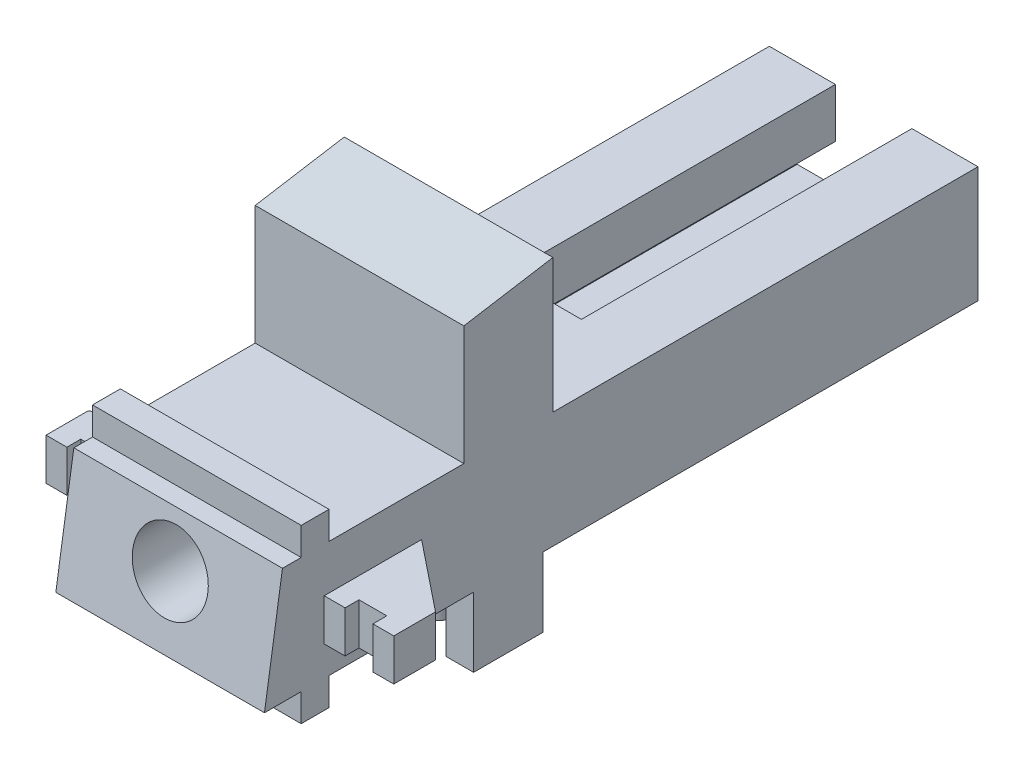
SolidWorks part; units mm, degrees
ref_plane "Front Plane" through (0, 0, 0) normal (0, 0, 1) x (1, 0, 0)
ref_plane "Top Plane" through (0, 0, 0) normal (0, 1, 0) x (1, 0, 0)
ref_plane "Right Plane" through (0, 0, 0) normal (1, 0, 0) x (0, 0, -1)
sketch "Sketch9" plane through (0, 0, 0) normal (0, 0, 1) x (1, 0, 0)
  line L1 (-7.5, 8.35) -> (7.5, 8.35)
  line L2 (-7.5, 8.35) -> (-7.5, 0)
  line L3 (-7.5, 0) -> (7.5, 0)
  line L4 (7.5, 8.35) -> (7.5, 0)
  line L5 (-7.5, 8.35) -> (7.5, 0) construction
  line L6 (-7.5, 0) -> (7.5, 8.35) construction
  point P0 (0, 4.175)
  point P19 (0, 0)
  dimension "D1" = 8.35
  dimension "D2" = 15
extrude "Boss-Extrude4" add sketch "Sketch9" along normal blind 50
sketch "Sketch7" plane through (0, 0, 0) normal (0, 0, 1) x (1, 0, 0)
  line L0 (-5.5, 2) -> (-5.5, 4.8)
  line L1 (-5.5, 4.8) -> (-2.75, 4.8)
  line L2 (-2.75, 4.8) -> (-2.75, 8.35)
  line L3 (-2.75, 8.35) -> (2.75, 8.35) construction
  line L4 (2.75, 8.35) -> (2.75, 4.8)
  line L5 (2.75, 4.8) -> (5.5, 4.8)
  line L6 (5.5, 4.8) -> (5.5, 2)
  line L7 (5.5, 2) -> (-5.5, 2)
  line L9 (7.5, 8.35) -> (-7.5, 8.35) construction
  line L11 (7.5, 0) -> (7.5, 8.35) construction
  line L13 (-2.75, 8.35) -> (2.75, 8.35)
  dimension "D1" = 2.8
  dimension "D2" = 2
  dimension "D3" = 11
  dimension "D4" = 5.5
  dimension "D5" = 2
extrude "Cut-Extrude4" cut sketch "Sketch7" along normal blind 23.76
sketch "Sketch21" plane through (-7.5, 0, 0) normal (-1, 0, 0) x (0, 0, 1)
  line L7 (50, 0) -> (51.2947, 0)
  line L8 (51.2947, 0) -> (50, 8.35)
  line L9 (50, 8.35) -> (50, 0)
extrude "Boss-Extrude9" add sketch "Sketch21" against normal up to surface (15 mm away) up to face at (7.5, 4.175, 25)
sketch "Sketch10" plane through (0, 0, 23.76) normal (0, 0, 1) x (1, 0, 0)
  line L0 (5.5, 2) -> (-5.5, 2) construction
  circle A0 centre (0, 4.7) radius 2.7
  dimension "D1" = 5.4
extrude "Cut-Extrude5" cut sketch "Sketch10" along normal up to surface (26.806 mm away)
sketch "Sketch12" plane through (7.5, 0, 0) normal (1, 0, 0) x (0, 0, -1)
  line L0 (-51.2947, 0) -> (0, 0) construction
  line L1 (-47, 5.14) -> (-44, 5.14)
  line L2 (-47, 5.14) -> (-47, 2.14)
  line L3 (-47, 2.14) -> (-44, 2.14)
  line L4 (-44, 5.14) -> (-44, 2.14)
  line L5 (-47, 5.14) -> (-44, 2.14) construction
  line L6 (-47, 2.14) -> (-44, 5.14) construction
  point P0 (-45.5, 3.64)
  dimension "D1" = 3
  dimension "D2" = 3
  dimension "D3" = 2.14
  dimension "D4" = 3
extrude "Boss-Extrude5" add sketch "Sketch12" along normal blind 5
ref_plane "Plane1" through (0, 0, 0) normal (1, 0, 0) x (0, 0, -1)
sketch "Sketch13" plane through (0, 0, 47) normal (0, 0, 1) x (1, 0, 0)
  line L1 (9, 5.14) -> (11, 5.14)
  line L2 (9, 5.14) -> (9, 2.14)
  line L3 (9, 2.14) -> (11, 2.14)
  line L4 (11, 5.14) -> (11, 2.14)
  line L6 (12.5, 5.14) -> (7.5, 5.14) construction
  line L7 (12.5, 2.14) -> (7.5, 2.14) construction
  point P8 (10, 5.14)
  point P9 (10, 5.14)
  dimension "D2" = 2
extrude "Cut-Extrude6" cut sketch "Sketch13" against normal blind 1
mirror "Mirror2" about plane through (0, 0, 0) normal (1, 0, 0) of "Boss-Extrude5"
mirror "Mirror4" about plane through (0, 0, 0) normal (1, 0, 0) of "Cut-Extrude6"
sketch "Sketch14" plane through (0, 5.14, 0) normal (0, 1, 0) x (1, 0, 0)
  line L0 (12.5, -44) -> (7.5, -40)
  line L1 (7.5, -50) -> (7.5, 0) construction
  line L2 (7.5, -40) -> (7.5, -44)
  line L3 (7.5, -44) -> (12.5, -44)
  dimension "D1" = 4
extrude "Boss-Extrude6" add sketch "Sketch14" against normal up to surface (3 mm away) up to face at (10, 2.14, 46)
mirror "Mirror5" about plane through (0, 0, 0) normal (1, 0, 0) of "Boss-Extrude6"
sketch "Sketch22" plane through (-7.5, 0, 0) normal (-1, 0, 0) x (0, 0, 1)
  line L0 (51.2947, 0) -> (0, 0) construction
  line L1 (48.6551, 0) -> (46.6551, 0)
  line L2 (48.6551, 0) -> (48.6551, -2)
  line L3 (48.6551, -2) -> (46.6551, -2)
  line L4 (46.6551, 0) -> (46.6551, -2)
  line L5 (48.6551, 0) -> (46.6551, -2) construction
  line L6 (48.6551, -2) -> (46.6551, 0) construction
  line L7 (50.6474, 4.175) -> (0, 4.175) construction
  line L8 (51.2947, 0) -> (50, 8.35) construction
  line L9 (0, 8.35) -> (0, 0) construction
  line L10 (48.6551, 10.35) -> (46.6551, 8.35) construction
  line L11 (48.6551, 8.35) -> (46.6551, 10.35) construction
  line L12 (46.6551, 8.35) -> (46.6551, 10.35)
  line L13 (48.6551, 10.35) -> (46.6551, 10.35)
  line L14 (48.6551, 8.35) -> (48.6551, 10.35)
  line L15 (48.6551, 8.35) -> (46.6551, 8.35)
  line L16 (50, 8.35) -> (0, 8.35) construction
  point P0 (47.6551, -1)
  point P18 (47.6551, 9.35)
  dimension "D1" = 2
extrude "Boss-Extrude10" add sketch "Sketch22" against normal up to surface (15 mm away) up to face at (7.5, 4.175, 25.3237)
sketch "Sketch23" plane through (0, 0, 0) normal (0, -1, 0) x (1, 0, 0)
  line L0 (-5.5, 23.76) -> (0, 23.76) construction
  line L2 (-7.5, 23.76) -> (7.5, 23.76) construction
  line L3 (7.5, 46.6551) -> (7.5, 0) construction
  line L4 (-7.5, 46.6551) -> (-7.5, 0) construction
  circle A0 centre (0, 29.26) radius 2.5
  dimension "D2" = 5
  dimension "D1" = 5.5
extrude "Cut-Extrude7" cut sketch "Sketch23" against normal up to surface (2 mm away)
sketch "Sketch24" plane through (0, 0, 0) normal (0, -1, 0) x (1, 0, 0)
  line L0 (5.5, 36.26) -> (7.5, 36.26)
  line L1 (7.5, 46.6551) -> (7.5, 0) construction
  line L2 (7.5, 36.26) -> (7.5, 31.26)
  line L3 (7.5, 31.26) -> (5.5, 31.26)
  line L4 (5.5, 36.26) -> (-5.5, 36.26)
  line L5 (-5.5, 36.26) -> (-5.5, 31.26)
  line L6 (-5.5, 31.26) -> (5.5, 31.26)
  line L7 (5.5, 31.26) -> (5.5, 36.26)
  line L8 (5.5, 36.26) -> (-5.5, 36.26) construction
  line L9 (-5.5, 36.26) -> (-5.5, 31.26)
  line L10 (-5.5, 31.26) -> (5.5, 31.26) construction
  line L11 (5.5, 31.26) -> (5.5, 36.26)
  line L12 (-5.5, 36.26) -> (-7.5, 36.26)
  line L13 (-7.5, 46.6551) -> (-7.5, 0) construction
  line L14 (-7.5, 36.26) -> (-7.5, 31.26)
  line L15 (-7.5, 31.26) -> (-5.5, 31.26)
  line L24 (2.5, 34.76) -> (-2.5, 34.76) construction
  line L25 (2.5, 34.76) -> (-2.5, 34.76) construction
  line L26 (2.5, 32.76) -> (-2.5, 32.76) construction
  line L27 (2.5, 32.76) -> (-2.5, 32.76) construction
  line L28 (2.5, 33.01) -> (-2.5, 33.01)
  line L29 (2.5, 34.51) -> (-2.5, 34.51)
  line L34 (0, 0) -> (0, 51.2947) construction
  line L35 (-7.5, 0) -> (7.5, 0) construction
  line L36 (7.5, 51.2947) -> (-7.5, 51.2947) construction
  arc A0 (2.5, 32.76) -> (2.5, 34.76) centre (2.5, 33.76) ccw construction
  arc A1 (2.5, 32.76) -> (2.5, 34.76) centre (2.5, 33.76) ccw construction
  arc A2 (-2.5, 34.76) -> (-2.5, 32.76) centre (-2.5, 33.76) ccw construction
  arc A3 (-2.5, 34.76) -> (-2.5, 32.76) centre (-2.5, 33.76) ccw construction
  arc A4 (-2.5, 34.51) -> (-2.5, 33.01) centre (-2.5, 33.76) ccw
  arc A5 (2.5, 33.01) -> (2.5, 34.51) centre (2.5, 33.76) ccw
  dimension "D1" = 0
  dimension "D2" = 0.25
extrude "Boss-Extrude11" add sketch "Sketch24" along normal blind 5
sketch "Sketch25" plane through (7.5, 0, 0) normal (1, 0, 0) x (0, 0, -1)
  line L0 (-31.26, -5) -> (-36.26, -5) construction
  line L1 (-30.5589, 8.35) -> (-36.9611, 8.35)
  line L2 (-30.5589, 8.35) -> (-30.5589, 17.9804)
  line L4 (-36.9611, 8.35) -> (-36.9611, 16.9226)
  line L7 (-46.6551, 8.35) -> (0, 8.35) construction
  line L9 (-48.9787, 14.9368) -> (-26.8966, 18.5855) construction
  line L10 (-36.9611, 16.9226) -> (-30.5589, 17.9804)
  point P7 (-33.76, -5)
  point P8 (-33.76, 8.35)
extrude "Boss-Extrude12" add sketch "Sketch25" against normal up to surface (15 mm away) up to face at (-7.5, 2.5063, 38.5984)
